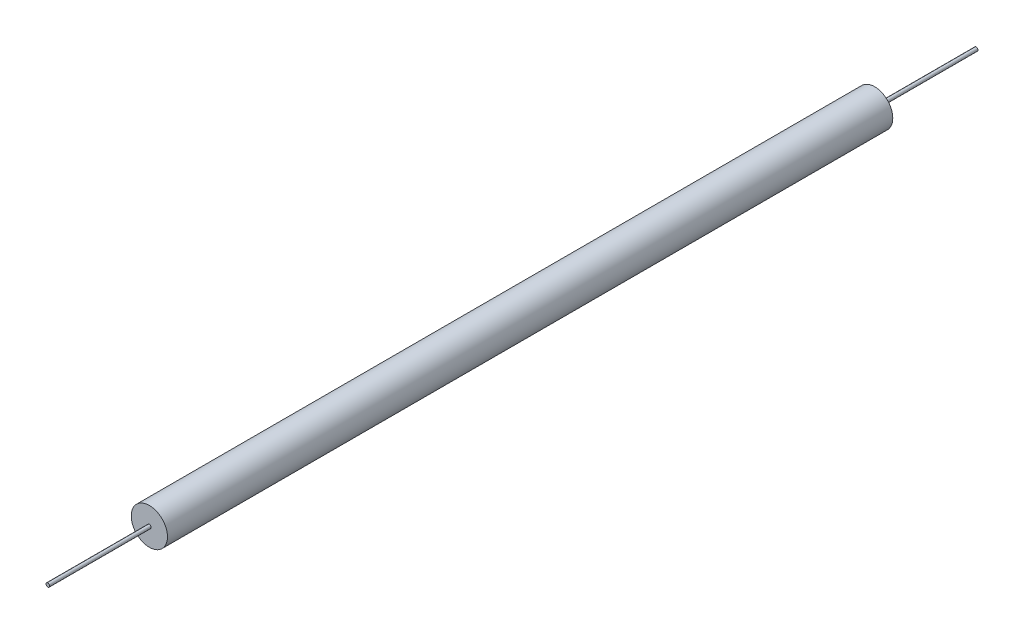
SolidWorks part; units mm, degrees
ref_plane "前视基准面" through (0, 0, 0) normal (0, 0, 1) x (1, 0, 0)
ref_plane "上视基准面" through (0, 0, 0) normal (0, 1, 0) x (1, 0, 0)
ref_plane "右视基准面" through (0, 0, 0) normal (1, 0, 0) x (0, 0, -1)
other "Configuration Table"
sketch "草图7" plane through (0, 0, 0) normal (0, 0, 1) x (1, 0, 0)
  circle A0 centre (0, 0) radius 5
extrude "凸台-拉伸4" add sketch "草图7" along normal blind 200
sketch "草图8" plane through (0, 0, 200) normal (0, 0, 1) x (1, 0, 0)
  circle A0 centre (0, 0) radius 0.5
extrude "凸台-拉伸5" add sketch "草图8" along normal blind 28
sketch "草图9" plane through (0, 0, 0) normal (0, 0, -1) x (-1, 0, 0)
  circle A0 centre (0, 0) radius 0.5
extrude "凸台-拉伸6" add sketch "草图9" along normal blind 84
sketch "草图10" plane through (0, 0, -84) normal (0, 0, -1) x (-1, 0, 0)
  circle A0 centre (0, 0) radius 0.5
extrude "切除-拉伸1" cut sketch "草图10" against normal blind 56
